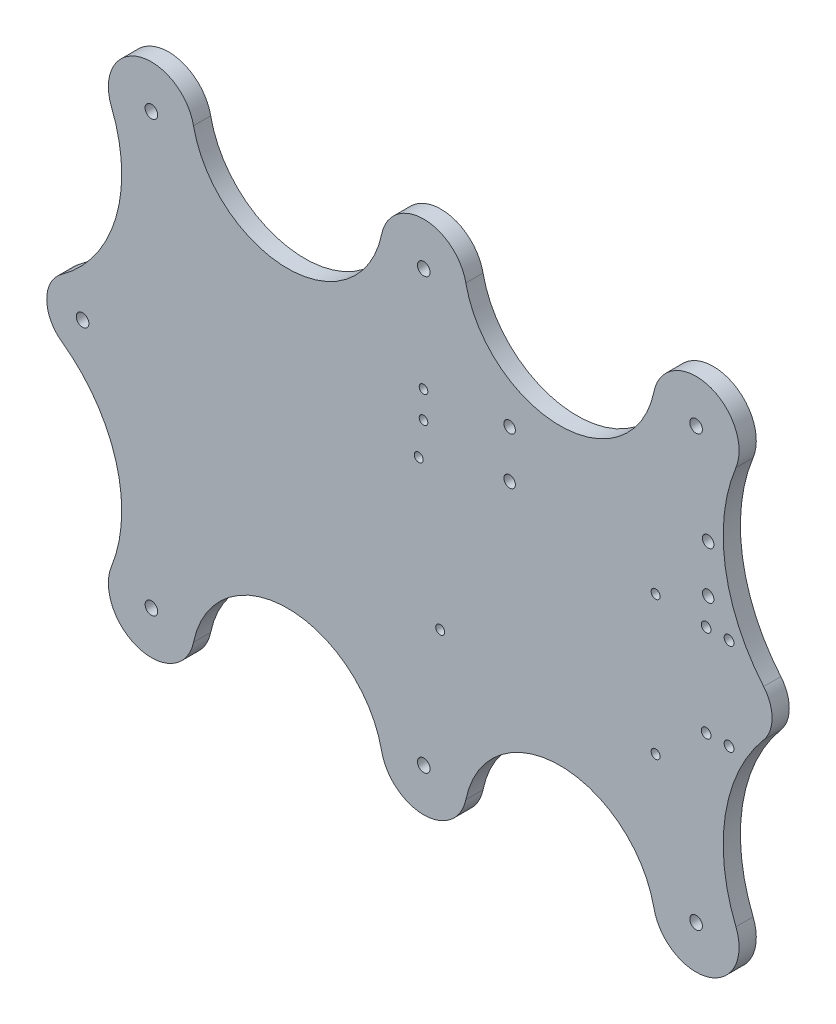
SolidWorks part; units mm, degrees
material "ABS"
ref_plane "Front Plane" through (0, 0, 0) normal (0, 0, 1) x (1, 0, 0)
ref_plane "Top Plane" through (0, 0, 0) normal (0, 1, 0) x (1, 0, 0)
ref_plane "Right Plane" through (0, 0, 0) normal (1, 0, 0) x (0, 0, -1)
sketch "Sketch2" plane through (0, 0, 0) normal (0, 0, 1) x (1, 0, 0)
  line L1 (-235.4178, -26.2985) -> (17.5822, -26.2985) construction
  arc A0 (14.6436, -34.3502) -> (14.6436, -18.2467) centre (5.0822, -26.2985) ccw construction
  arc A1 (14.6436, -34.3502) -> (14.6436, -18.2467) centre (5.0822, -26.2985) ccw
  arc A2 (14.6436, -34.3502) -> (4.9734, -95.6385) centre (60.5381, -72.9986) ccw
  arc A3 (14.6436, -34.3502) -> (0.5381, -72.9986) centre (60.5381, -72.9986) ccw construction
  arc A5 (-23.6085, -104.3288) -> (-89.2271, -104.3288) centre (-56.4178, -111.0964) ccw
  arc A7 (-118.6085, -104.3288) -> (-184.2271, -104.3288) centre (-151.4178, -111.0964) ccw
  arc A9 (-212.8436, -95.7244) -> (-230.1869, -36.4676) centre (-259.2631, -77.144) ccw
  arc A10 (-230.1869, -16.1294) -> (-230.1869, -36.4676) centre (-222.9178, -26.2985) ccw
  arc A11 (-212.8436, -95.7244) -> (-184.2271, -104.3288) centre (-198.9178, -101.2985) ccw
  arc A12 (-118.6085, -104.3288) -> (-89.2271, -104.3288) centre (-103.9178, -101.2985) ccw
  arc A13 (-23.6085, -104.3288) -> (4.9734, -95.6385) centre (-8.9178, -101.2985) ccw
  arc A14 (-23.6085, 51.7318) -> (4.9734, 43.0415) centre (-8.9178, 48.7015) cw
  arc A15 (-118.6085, 51.7318) -> (-89.2271, 51.7318) centre (-103.9178, 48.7015) cw
  arc A16 (-212.8436, 43.1274) -> (-184.2271, 51.7318) centre (-198.9178, 48.7015) cw
  arc A17 (-212.8436, 43.1274) -> (-230.1869, -16.1294) centre (-259.2631, 24.547) cw
  arc A18 (-118.6085, 51.7318) -> (-184.2271, 51.7318) centre (-151.4178, 58.4995) cw
  arc A19 (-23.6085, 51.7318) -> (-89.2271, 51.7318) centre (-56.4178, 58.4995) cw
  arc A20 (14.6436, -18.2467) -> (4.9734, 43.0415) centre (60.5381, 20.4016) cw
extrude "Boss-Extrude1" add sketch "Sketch2" along normal blind 6 contours A1 A20 A14 A19 A15 A18 A16 A17 A10 A9 A11 A7 A12 A5 A13 A2
sketch "Sketch3" plane through (0, 0, 6) normal (0, 0, 1) x (1, 0, 0)
  circle A0 centre (-222.9178, -26.2985) radius 2.2
  circle A1 centre (-198.9178, -101.2985) radius 2.2
  circle A2 centre (-103.9178, -101.2985) radius 2.2
  circle A3 centre (-8.9178, -101.2985) radius 2.2
  circle A8 centre (-5.4178, -10.2985) radius 1.7
  circle A9 centre (-5.4178, -42.2985) radius 1.7
  circle A10 centre (2.5822, -42.2985) radius 1.7
  circle A11 centre (2.5822, -10.2985) radius 1.7
  circle A12 centre (-8.9178, 48.7015) radius 2.2
  arc A13 (-6.7178, 48.7015) -> (-11.1178, 48.7015) centre (-8.9178, 48.7015) ccw construction
  circle A14 centre (-103.9178, 48.7015) radius 2.2
  circle A15 centre (-198.9178, 48.7015) radius 2.2
extrude "Cut-Extrude1" cut sketch "Sketch3" against normal through all
ref_plane "Plane1" through (0, -26.2985, 0) normal (0, 1, 0) x (1, 0, 0)
ref_plane "Plane2" through (-103.9178, 0, 0) normal (1, 0, 0) x (0, 0, -1)
sketch "Sketch5" plane through (0, 0, 6) normal (0, 0, 1) x (1, 0, 0)
  circle A0 centre (-89.6279, 15.9096) radius 2
  circle A1 centre (-89.6279, -0.5904) radius 2
  circle A2 centre (-20.3779, -0.5904) radius 2
  circle A3 centre (-20.3779, 15.9096) radius 2
sketch "Sketch6" plane through (0, 0, 6) normal (0, 0, 1) x (1, 0, 0)
  circle A0 centre (-33.0402, -57.4666) radius 1.5621
  circle A1 centre (-108.1734, -57.4666) radius 1.5621
  circle A2 centre (-115.6664, -9.1304) radius 1.5621
  circle A3 centre (-33.0402, -9.1304) radius 1.5621
sketch "Sketch7" plane through (0, 0, 6) normal (0, 0, 1) x (1, 0, 0)
  circle A0 centre (-13.6788, 7.7419) radius 1.5
  circle A1 centre (-13.6788, -1.6227) radius 1.5
sketch "Sketch8" plane through (0, 0, 6) normal (0, 0, 1) x (1, 0, 0)
  circle A0 centre (-47.8075, 15.9096) radius 2
  circle A1 centre (-47.8075, -0.5904) radius 2
  circle A2 centre (-117.0575, -0.5904) radius 2
  circle A3 centre (-117.0575, 15.9096) radius 2
sketch "Sketch9" plane through (0, 0, 6) normal (0, 0, 1) x (1, 0, 0)
  circle A0 centre (-103.995, 12.2819) radius 1.5
  circle A1 centre (-103.995, 2.9173) radius 1.5
  circle A2 centre (-103.9178, 48.7015) radius 2.2 construction
  dimension "D1" = 36.4196
  dimension "D2" = 45.7842
extrude "Cut-Extrude7" cut sketch "Sketch9" against normal through all
sketch "Sketch10" plane through (0, 0, 6) normal (0, 0, 1) x (1, 0, 0)
  circle A0 centre (-4.7026, 15.9096) radius 2
  circle A1 centre (-4.7026, -0.5904) radius 2
  circle A2 centre (-73.9526, 15.9096) radius 2
  circle A3 centre (-73.9526, -0.5904) radius 2
extrude "Cut-Extrude8" cut sketch "Sketch10" against normal through all
sketch "Sketch11" plane through (0, 0, 6) normal (0, 0, 1) x (1, 0, 0)
  circle A0 centre (-23.0402, -9.1304) radius 1.5621
  circle A1 centre (-23.0402, -57.4666) radius 1.5621
  circle A2 centre (-105.6664, -9.1304) radius 1.5621
  circle A3 centre (-98.1734, -57.4666) radius 1.5621
extrude "Cut-Extrude9" cut sketch "Sketch11" against normal through all
